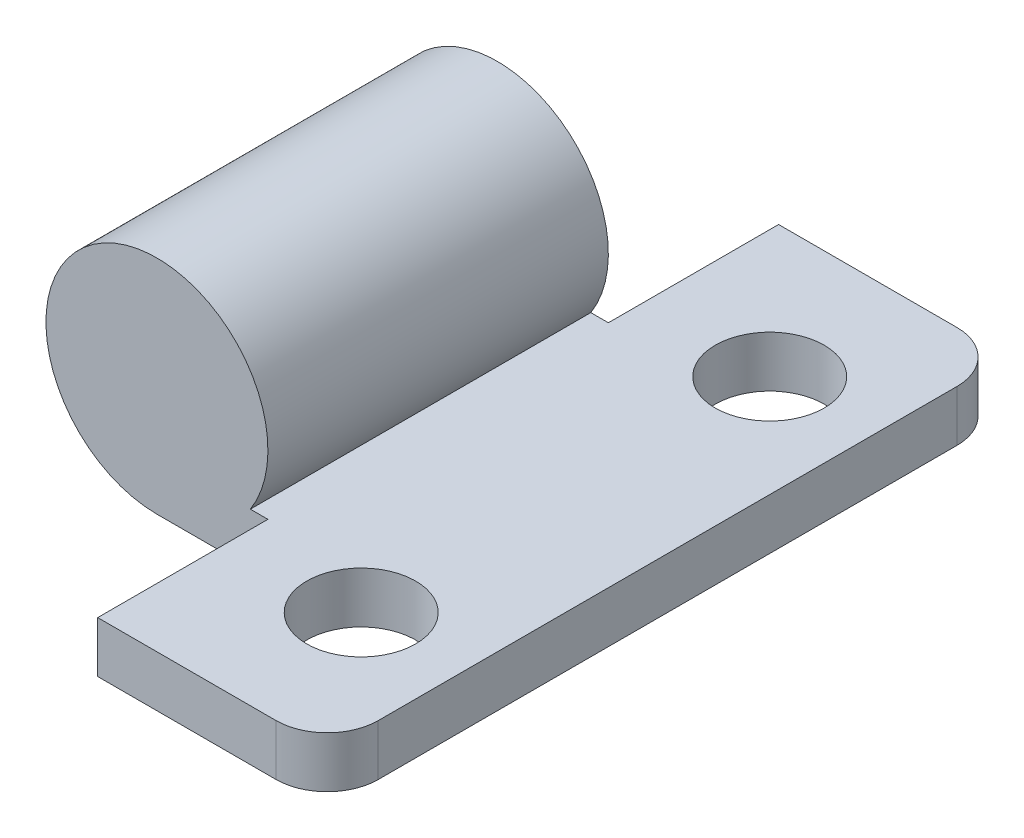
SolidWorks part; units mm, degrees
material "6061 合金"
ref_plane "前视基准面" through (0, 0, 0) normal (0, 0, 1) x (1, 0, 0)
ref_plane "上视基准面" through (0, 0, 0) normal (0, 1, 0) x (1, 0, 0)
ref_plane "右视基准面" through (0, 0, 0) normal (1, 0, 0) x (0, 0, -1)
sketch "草图1" plane through (0, 0, 0) normal (0, 0, 1) x (1, 0, 0)
  line L0 (0, -3.26) -> (10, -3.26)
  line L1 (10, -3.26) -> (10, -1.76)
  line L2 (10, -1.76) -> (2.7441, -1.76)
  arc A0 (2.7441, -1.76) -> (0, -3.26) centre (0, 0) ccw
  dimension "D1" = 6.52
  dimension "D2" = 1.5
  dimension "D3" = 10
extrude "凸台-拉伸1" add sketch "草图1" along normal mid plane 20
sketch "草图2" plane through (0, -1.76, 0) normal (0, 1, 0) x (1, 0, 0)
  line L0 (0, 0) -> (10, 0) construction
  line L1 (10, -10) -> (10, 10) construction
  line L2 (3.26, -10) -> (3.26, 10) construction
  line L3 (-3.26, 10) -> (3.26, 10)
  line L4 (-3.26, 10) -> (-3.26, 5)
  line L5 (-3.26, 5) -> (3.26, 5)
  line L6 (3.26, 10) -> (3.26, 5)
  line L7 (-3.26, -10) -> (3.26, -10) construction
  line L8 (-3.26, -10) -> (3.26, -10)
  line L9 (-3.26, -10) -> (-3.26, -5)
  line L10 (-3.26, -5) -> (3.26, -5)
  line L11 (3.26, -10) -> (3.26, -5)
  line L12 (-3.26, 10) -> (-3.26, -10) construction
  circle A0 centre (7, 6) radius 1.6
  circle A1 centre (7, -6) radius 1.6
  dimension "D1" = 3.2
  dimension "D3" = 7
  dimension "D2" = 6
  dimension "D4" = 5
  dimension "D5" = 5
extrude "切除-拉伸1" cut sketch "草图2" against normal through all both and the other way through all
fillet "圆角1" radius 1.5 2 edges at (10, -2.51, -10) (10, -2.51, 10)
